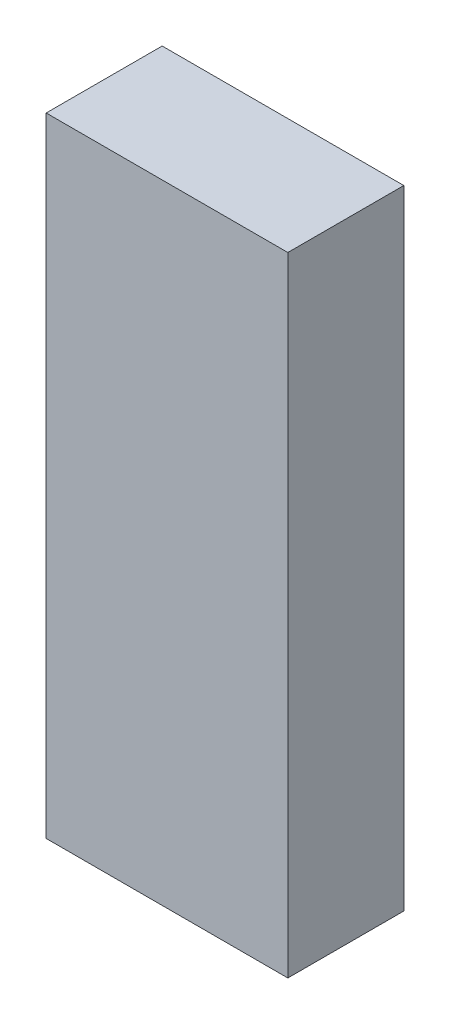
SolidWorks part; units mm, degrees
ref_plane "Plan de face" through (0, 0, 0) normal (0, 0, 1) x (1, 0, 0)
ref_plane "Plan de dessus" through (0, 0, 0) normal (0, 1, 0) x (1, 0, 0)
ref_plane "Plan de droite" through (0, 0, 0) normal (1, 0, 0) x (0, 0, -1)
sketch "Esquisse1" plane through (0, 0, 0) normal (0, 0, 1) x (1, 0, 0)
  line L1 (0, 0) -> (-25, 0)
  line L2 (0, 0) -> (0, 65)
  line L3 (0, 65) -> (-25, 65)
  line L4 (-25, 0) -> (-25, 65)
  dimension "D1" = 65
  dimension "D2" = 25
extrude "Boss.-Extru.1" add sketch "Esquisse1" along normal blind 12
